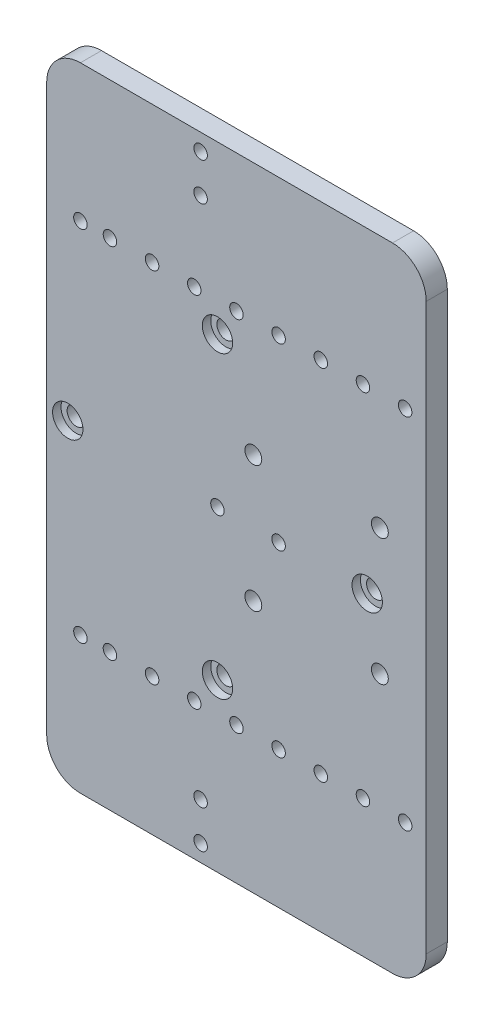
SolidWorks part; units mm, degrees
ref_plane "前视基准面" through (0, 0, 0) normal (0, 0, 1) x (1, 0, 0)
ref_plane "上视基准面" through (0, 0, 0) normal (0, 1, 0) x (1, 0, 0)
ref_plane "右视基准面" through (0, 0, 0) normal (1, 0, 0) x (0, 0, -1)
sketch "草图1" plane through (0, 0, 0) normal (0, 0, 1) x (1, 0, 0)
  line L1 (0, 0) -> (90, 0)
  line L2 (0, 0) -> (0, -150)
  line L3 (0, -150) -> (90, -150)
  line L4 (90, 0) -> (90, -150)
  circle A4 centre (79, -60) radius 2
  circle A5 centre (79, -90) radius 2
  circle A12 centre (49, -60) radius 2
  circle A13 centre (49, -90) radius 2
  circle A14 centre (40.5, -39.5) radius 2.15
  circle A15 centre (40.5, -110.5) radius 2.15
  circle A16 centre (76, -75) radius 2.15
  circle A17 centre (5, -75) radius 2.15
  circle A18 centre (85, -117.5) radius 1.6
  circle A19 centre (75, -117.5) radius 1.6
  circle A20 centre (65, -117.5) radius 1.6
  circle A21 centre (55, -117.5) radius 1.6
  circle A22 centre (45, -117.5) radius 1.6
  circle A23 centre (85, -32.5) radius 1.6
  circle A24 centre (75, -32.5) radius 1.6
  circle A25 centre (65, -32.5) radius 1.6
  circle A26 centre (55, -32.5) radius 1.6
  circle A27 centre (45, -32.5) radius 1.6
  circle A28 centre (35, -117.5) radius 1.6
  circle A29 centre (25, -117.5) radius 1.6
  circle A30 centre (15, -117.5) radius 1.6
  circle A31 centre (35, -32.5) radius 1.6
  circle A32 centre (25, -32.5) radius 1.6
  circle A33 centre (15, -32.5) radius 1.6
  circle A34 centre (8, -117.5) radius 1.6
  circle A35 centre (8, -32.5) radius 1.6
  circle A36 centre (36.5, -4) radius 1.6
  circle A37 centre (36.5, -13) radius 1.6
  circle A38 centre (36.5, -137) radius 1.6
  circle A39 centre (36.5, -146) radius 1.6
  circle A40 centre (55, -75) radius 1.6
  circle A41 centre (40.5, -75) radius 1.6
  dimension "D1" = 150
  dimension "D15" = 2
  dimension "D5" = 30
  dimension "D16" = 2
  dimension "D17" = 2
  dimension "D18" = 39.5
  dimension "D7" = 49
  dimension "D19" = 71
  dimension "D21" = 71
  dimension "D3" = 75
  dimension "D4" = 32.5
  dimension "D6" = 3.2
  dimension "D12" = 5
  dimension "D23" = 7
  dimension "D24" = 4
  dimension "D25" = 36.5
  dimension "D28" = 4
  dimension "D29" = 9
  dimension "D30" = 50
  dimension "D31" = 35.5
  dimension "D2" = 90
  dimension "D8" = 60
  dimension "D9" = 5
  dimension "D10" = 30
  dimension "D11" = 2
  dimension "D13" = 4
  dimension "D14" = 2
  dimension "D20" = 40.5
  dimension "D22" = 5
  dimension "D26" = 2
  dimension "D27" = 2
extrude "凸台-拉伸1" add sketch "草图1" along normal blind 5
fillet "圆角1" radius 8 4 edges at (0, -150, 2.5) (90, -150, 2.5) (90, 0, 2.5) (0, 0, 2.5)
sketch "草图2" plane through (0, 0, 5) normal (0, 0, 1) x (1, 0, 0)
  circle A0 centre (40.5, -39.5) radius 3.6
  circle A1 centre (76, -75) radius 3.6
  circle A2 centre (5, -75) radius 3.6
  circle A3 centre (40.5, -110.5) radius 3.6
  circle A5 centre (40.5, -39.5) radius 2.15 construction
  circle A6 centre (76, -75) radius 2.15 construction
  circle A7 centre (40.5, -110.5) radius 2.15 construction
  circle A8 centre (5, -75) radius 2.15 construction
extrude "切除-拉伸1" cut sketch "草图2" against normal blind 2
